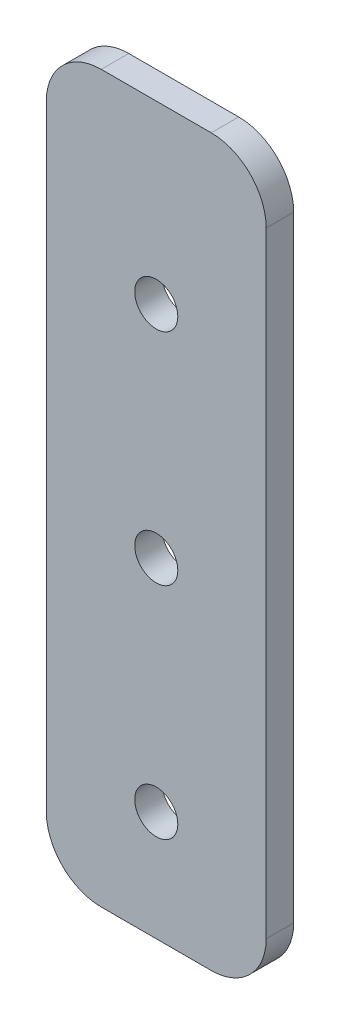
SolidWorks part; units mm, degrees
ref_plane "Front Plane" through (0, 0, 0) normal (0, 0, 1) x (1, 0, 0)
ref_plane "Top Plane" through (0, 0, 0) normal (0, 1, 0) x (1, 0, 0)
ref_plane "Right Plane" through (0, 0, 0) normal (1, 0, 0) x (0, 0, -1)
sketch "Sketch1" plane through (0, 0, 0) normal (0, 0, 1) x (1, 0, 0)
  line L1 (0, 0) -> (25.4, 0)
  line L2 (0, 0) -> (0, 83.82)
  line L3 (0, 83.82) -> (25.4, 83.82)
  line L4 (25.4, 0) -> (25.4, 83.82)
  dimension "D1" = 25.4
  dimension "D2" = 83.82
extrude "Boss-Extrude1" add sketch "Sketch1" along normal blind 3.175
sketch "Sketch2" plane through (0, 0, 3.175) normal (0, 0, 1) x (1, 0, 0)
  line L0 (25.4, 0) -> (25.4, 83.82) construction
  line L1 (0, 0) -> (25.4, 0) construction
  circle A0 centre (12.7, 12.7) radius 2.4892
  circle A1 centre (12.7, 38.1) radius 2.4892
  circle A2 centre (12.7, 63.5) radius 2.4892
  dimension "D1" = 12.7
  dimension "D3" = 4.9784
  dimension "D2" = 12.7
  dimension "D4" = 3
extrude "Cut-Extrude1" cut sketch "Sketch2" against normal through all
fillet "Fillet1" radius 6.35 4 edges at (25.4, 83.82, 1.5875) (25.4, 0, 1.5875) (0, 0, 1.5875) (0, 83.82, 1.5875)
